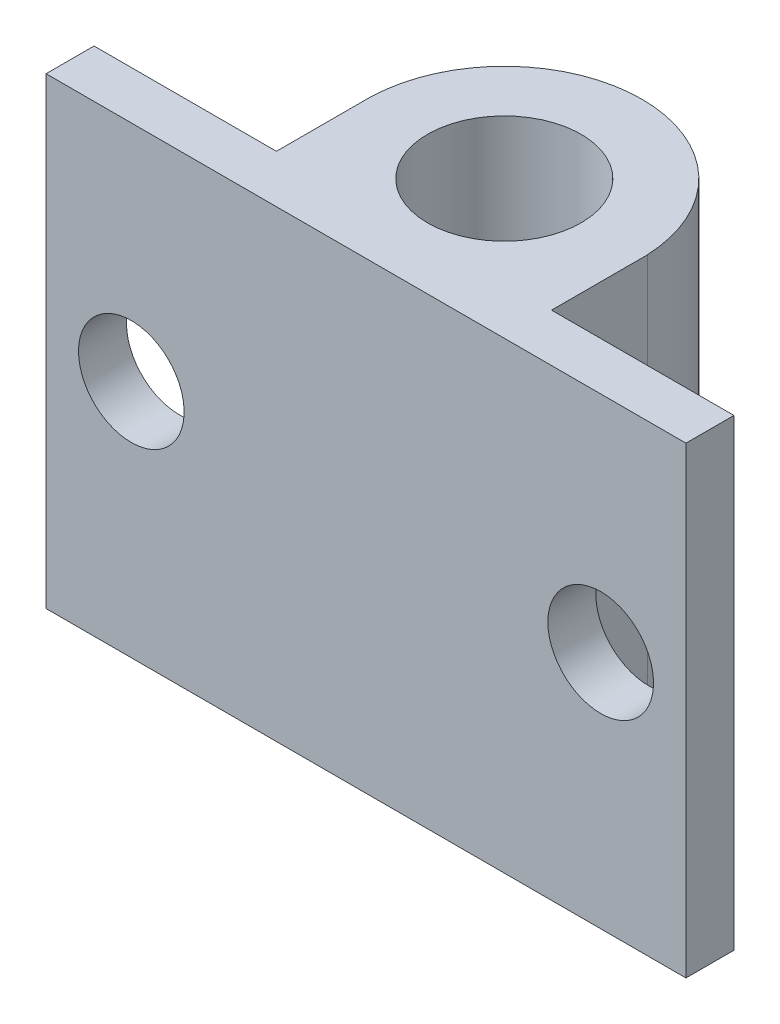
SolidWorks part; units mm, degrees
ref_plane "Front" through (0, 0, 0) normal (0, 0, 1) x (1, 0, 0)
ref_plane "Top" through (0, 0, 0) normal (0, 1, 0) x (1, 0, 0)
ref_plane "Right" through (0, 0, 0) normal (1, 0, 0) x (0, 0, -1)
sketch "Sketch1" plane through (0, 0, 0) normal (0, 1, 0) x (1, 0, 0)
  line L0 (-4.3, 0) -> (-4.3, -2.8228)
  line L1 (-10, -2.8228) -> (10, -2.8228)
  line L2 (-10, -2.8228) -> (-10, -4.3228)
  line L3 (-10, -4.3228) -> (10, -4.3228)
  line L4 (10, -2.8228) -> (10, -4.3228)
  line L5 (4.3, 0) -> (4.3, -2.8228)
  circle A0 centre (0, 0) radius 2.4
  circle A1 centre (0, 0) radius 4.3
  point P8 (-4.3, 0)
  dimension "D1" = 4.8
  dimension "D2" = 1.5
  dimension "D3" = 20
  dimension "D4" = 10
extrude "Boss-Extrude1" add sketch "Sketch1" along normal blind 14.478 contours L1 A1 A0
sketch "Sketch2" plane through (0, 0, 2.8228) normal (0, 0, -1) x (-1, 0, 0)
  line L1 (-3.2437, 14.478) -> (-4.3, 14.478)
  line L2 (-3.2437, 14.478) -> (-3.2437, 0)
  line L3 (-3.2437, 0) -> (-4.3, 0)
  line L4 (-4.3, 14.478) -> (-4.3, 0)
extrude "Boss-Extrude2" add sketch "Sketch2" along normal blind 3
sketch "Sketch3" plane through (0, 0, 2.8228) normal (0, 0, -1) x (-1, 0, 0)
  line L1 (3.2437, 14.478) -> (4.3, 14.478)
  line L2 (3.2437, 14.478) -> (3.2437, 0)
  line L3 (3.2437, 0) -> (4.3, 0)
  line L4 (4.3, 14.478) -> (4.3, 0)
extrude "Boss-Extrude3" add sketch "Sketch3" along normal blind 3
sketch "Sketch4" plane through (0, 0, 2.8228) normal (0, 0, -1) x (-1, 0, 0)
  line L0 (10, 14.478) -> (10, 0) construction
  line L1 (10, 14.478) -> (4.3, 14.478) construction
  line L2 (0, 14.478) -> (0, 0)
  line L3 (4.2963, 14.478) -> (-4.2963, 14.478) construction
  circle A0 centre (7.3356, 7.478) radius 1.651
  circle A1 centre (-7.3356, 7.478) radius 1.651
  dimension "D1" = 3.302
  dimension "D2" = 2.6644
  dimension "D3" = 7
extrude "Cut-Extrude1" cut sketch "Sketch4" against normal blind 3 contours A1 | A0
